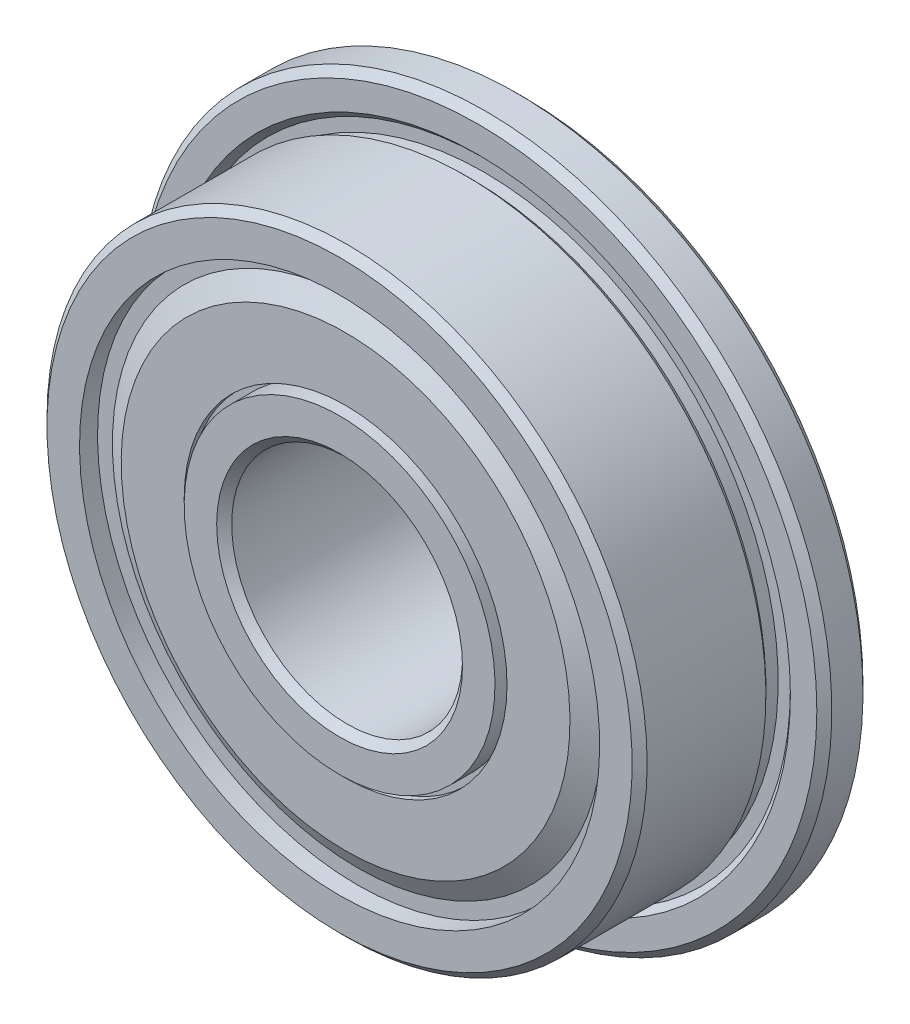
SolidWorks part; units mm, degrees
ref_plane "Front Plane" through (0, 0, 0) normal (0, 0, 1) x (1, 0, 0)
ref_plane "Top Plane" through (0, 0, 0) normal (0, 1, 0) x (1, 0, 0)
ref_plane "Right Plane" through (0, 0, 0) normal (1, 0, 0) x (0, 0, -1)
sketch "Sketch1" plane through (0, 0, 0) normal (1, 0, 0) x (0, 0, -1)
  line L0 (0, 6.5) -> (0, -6.5) construction
  line L1 (-2, 6.5) -> (2, 6.5) construction
  line L2 (0, 0) -> (2, 0) construction
  line L3 (2, 7.5) -> (2, -7.5) construction
  line L4 (2, -7.5) -> (1, -7.5) construction
  line L5 (2, 2.5) -> (0, 2.5) construction
  line L6 (2, 2.5) -> (2, -2.5) construction
  dimension "OD" = 13
  dimension "Width" = 4
  dimension "Flange Thickness" = 1
  dimension "ID" = 5
  dimension "Flange OD" = 15
sketch "Sketch2" plane through (0, 0, 0) normal (1, 0, 0) x (0, 0, -1)
  line L0 (2, 7.5) -> (1, 7.5)
  line L1 (1, 7.5) -> (1, 6.7652)
  line L2 (0.7348, 6.5) -> (-2, 6.5)
  line L3 (-2, 6.5) -> (-2, 5.2)
  line L4 (-2, 5.2) -> (-0.7141, 5.2)
  line L5 (2, 7.5) -> (2, -7.5) construction
  line L6 (2, 5.2) -> (2, 7.5)
  line L7 (2, 2.5) -> (-2, 2.5)
  line L8 (-2, 2.5) -> (-2, 3.8)
  line L9 (-2, 3.8) -> (-0.7141, 3.8)
  line L10 (2, 3.8) -> (2, 2.5)
  line L11 (0, 6.5) -> (0, 2.5) construction
  line L12 (-1, 4.5) -> (1, 4.5) construction
  line L13 (0.7141, 5.2) -> (2, 5.2)
  line L14 (0.7141, 3.8) -> (2, 3.8)
  line L15 (1, 6.7652) -> (1.1326, 6.6326)
  line L16 (1.1326, 6.6326) -> (1.1326, 6.3674)
  line L17 (1.1326, 6.3674) -> (0.8674, 6.3674)
  line L18 (0.8674, 6.3674) -> (0.7348, 6.5)
  line L19 (1, 6.5) -> (1.1326, 6.3674) construction
  line L20 (1.1326, 6.6326) -> (0.8674, 6.3674) construction
  line L21 (0.7348, 6.5) -> (1, 6.5) construction
  line L22 (1, 6.5) -> (1, 6.7652) construction
  line L23 (-2, 0) -> (2, 0) construction
  circle A0 centre (0, 4.5) radius 1 construction
  arc A1 (-0.7141, 5.2) -> (0.7141, 5.2) centre (0, 4.5) cw
  arc A2 (-0.7141, 3.8) -> (0.7141, 3.8) centre (0, 4.5) ccw
  dimension "Ball Dia." = 2
  dimension "D2" = 135
  dimension "D3" = 0.375
  dimension "Race Thikness" = 1.3
  dimension "D4" = 1.4
revolve "Revolve1" add sketch "Sketch2" angle 360 about L2
fillet "Fillet1" radius 0.1625 3 edges at (0, -7.5, -2) (0, -7.5, -1) (0, -6.5, 2) profile chamfer
sketch "Sketch3" plane through (0, 0, 0) normal (0, 0, 1) x (1, 0, 0)
  line L0 (-2.5, 0) -> (2.5, 0) construction
  line L1 (-6.5, 0) -> (6.5, 0) construction
  point P5 (0, 0)
  dimension "ID2" = 5
  dimension "OD2" = 13
fillet "Fillet2" radius 0.1625 2 edges at (0, -2.5, -2) (0, -2.5, 2) profile chamfer
sketch "Sketch7" plane through (0, 0, 0) normal (0, 0, 1) x (1, 0, 0)
  line L0 (0, 5.5) -> (0, 3.5)
  line L1 (0, 7.5) -> (0, -7.5) construction
  line L2 (-1.2536, 5.5) -> (0, 0) construction
  line L3 (0, 0) -> (1.2536, 5.5) construction
  line L4 (1.2536, 5.5) -> (-1.2536, 5.5) construction
  circle A0 centre (0, 4.5) radius 1 construction
  circle A1 centre (0, 0) radius 5.5 construction
  circle A2 centre (0, 0) radius 3.5 construction
  arc A4 (0, 5.5) -> (0, 3.5) centre (0, 4.5) ccw
  dimension "D1" = 25.679
revolve "Revolve3" add sketch "Sketch7" angle 360 about L0
pattern_circular "CirPattern3" count 10 over 360 about axis through (0, 0, 0) along (0, 0, 1) of bodies 107
sketch "Sketch8" plane through (0, 0, 0) normal (1, 0, 0) x (0, 0, -1)
  line L1 (-2, 5.2) -> (-1.48, 5.2)
  line L2 (-2, 5.2) -> (-2, 5.6333)
  line L3 (-2, 5.6333) -> (-1.48, 5.6333)
  line L4 (-1.48, 5.2) -> (-1.48, 5.6333)
  line L5 (2, 5.2) -> (1.48, 5.2)
  line L6 (2, 5.2) -> (2, 5.6333)
  line L7 (2, 5.6333) -> (1.48, 5.6333)
  line L8 (1.48, 5.2) -> (1.48, 5.6333)
  line L9 (2, 3.8) -> (1.48, 3.8)
  line L10 (2, 3.8) -> (2, 3.3667)
  line L11 (2, 3.3667) -> (1.48, 3.3667)
  line L12 (1.48, 3.8) -> (1.48, 3.3667)
  line L13 (-2, 3.8) -> (-1.48, 3.8)
  line L14 (-2, 3.8) -> (-2, 3.3667)
  line L15 (-2, 3.3667) -> (-1.48, 3.3667)
  line L16 (-1.48, 3.8) -> (-1.48, 3.3667)
  dimension "D1" = 0.4333
  dimension "D2" = 0.52
revolve "Cut-Revolve1" cut sketch "Sketch8" angle 360 about L2
sketch "Sketch9" plane through (0, 0, 0) normal (1, 0, 0) x (0, 0, -1)
  line L0 (-1.48, 5.6333) -> (-1.48, 5.2762)
  line L1 (-1.48, 5.2762) -> (-1.74, 4.8259)
  line L2 (-1.74, 4.8259) -> (-1.74, 3.4967)
  line L3 (1.74, 3.4967) -> (1.74, 3.3667) construction
  line L4 (1.48, 5.6333) -> (1.48, 5.2762)
  line L5 (1.48, 5.2762) -> (1.74, 4.8259)
  line L6 (1.74, 4.8259) -> (1.74, 3.4967)
  line L7 (2, 3.3667) -> (1.48, 3.3667) construction
  line L8 (-1.61, 5.6333) -> (-1.61, 5.311)
  line L9 (-1.61, 5.311) -> (-1.87, 4.8607)
  line L10 (-1.87, 4.8607) -> (-1.87, 3.4967)
  line L11 (-1.48, 5.6333) -> (-1.61, 5.6333)
  line L12 (-1.74, 3.4967) -> (-1.87, 3.4967)
  line L13 (1.61, 5.6333) -> (1.61, 5.311)
  line L14 (1.61, 5.311) -> (1.87, 4.8607)
  line L15 (1.87, 4.8607) -> (1.87, 3.4967)
  line L16 (1.48, 5.6333) -> (1.61, 5.6333)
  line L17 (1.74, 3.4967) -> (1.87, 3.4967)
  line L18 (-1.48, 5.2762) -> (-1.48, 2.5308) construction
  line L19 (1.48, 5.2762) -> (1.48, 5.6333) construction
  line L20 (-1.48, 3.3667) -> (-2, 3.3667) construction
  line L22 (-1.74, 3.4967) -> (-1.74, 3.3667) construction
  dimension "D2" = 150
  dimension "D1" = 150
  dimension "D5" = 0.52
  dimension "D3" = 0.13
  dimension "D4" = 0.13
  dimension "D6" = 0.3571
revolve "Revolve4" add sketch "Sketch9" angle 360 about L2
equation "\"D1@Fillet1\"=\"Race Thikness@Sketch2\"/8"
equation "\"ID2@Sketch3\" = \"ID@Sketch1\""
equation "\"OD2@Sketch3\" = \"OD@Sketch1\""
equation "\"D1@Fillet2\"=\"Race Thikness@Sketch2\"/8"
equation "\"D1@CirPattern3\"=360/\"D1@Sketch7\"-4"
equation "\"D1@Sketch8\"=\"Race Thikness@Sketch2\"/3"
equation "\"D2@Sketch8\"=\"Race Thikness@Sketch2\"/2.5"
equation "\"D3@Sketch9\"=\"D5@Sketch9\"/4"
equation "\"D4@Sketch9\"=\"D5@Sketch9\"/4"
equation "\"D1@Sketch9\"=\"D2@Sketch9\""
equation "\"Ball Dia.@Sketch2\" = \"D1@Sketch2\"*.5"
equation "\"D4@Sketch2\"=((\"OD@Sketch1\"-\"ID@Sketch1\")/2)*.35"
